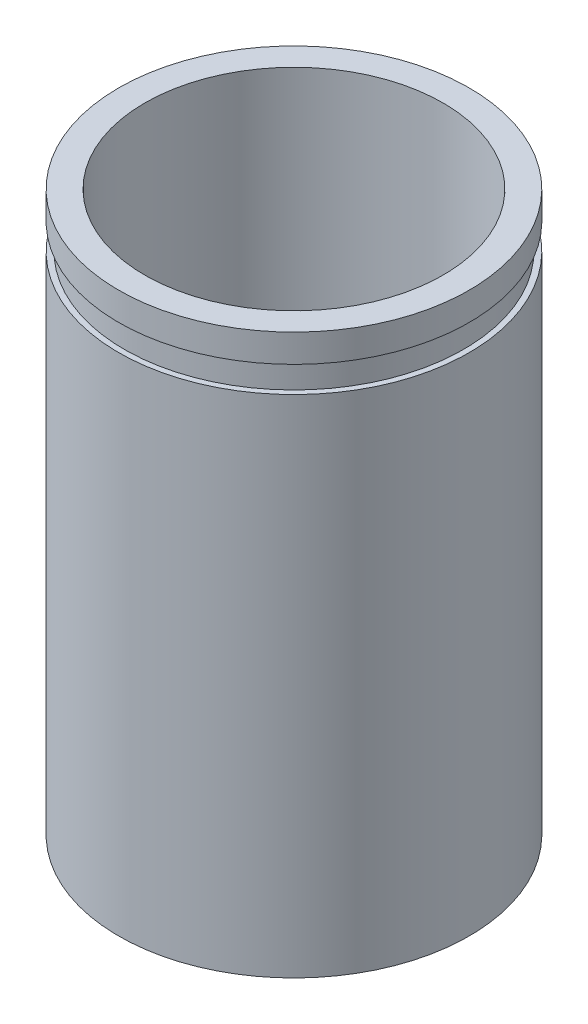
SolidWorks part; units mm, degrees
ref_plane "Front Plane" through (0, 0, 0) normal (0, 0, 1) x (1, 0, 0)
ref_plane "Top Plane" through (0, 0, 0) normal (0, 1, 0) x (1, 0, 0)
ref_plane "Right Plane" through (0, 0, 0) normal (1, 0, 0) x (0, 0, -1)
sketch "Sketch1" plane through (0, 0, 0) normal (0, 0, 1) x (1, 0, 0)
  line L0 (17.2728, 134.2124) -> (24.2728, 134.2124)
  line L1 (24.2728, 134.2124) -> (24.2728, 126.7124)
  line L2 (24.2728, 126.7124) -> (22.7728, 126.7124)
  line L3 (22.7728, 126.7124) -> (22.7728, 119.7124)
  line L4 (22.7728, 119.7124) -> (24.2728, 119.7124)
  line L5 (24.2728, 119.7124) -> (24.2728, -15.7876)
  line L6 (24.2728, -15.7876) -> (17.2728, -15.7876)
  line L7 (17.2728, -15.7876) -> (17.2728, 134.2124)
  line L8 (-22.7272, 134.2124) -> (-22.7272, -15.7876)
  dimension "D1" = 7
  dimension "D2" = 7.5
  dimension "D3" = 1.5
  dimension "D4" = 7
  dimension "D5" = 150
  dimension "D6" = 7
  dimension "D7" = 40
revolve "Revolve1" add sketch "Sketch1" angle 360 about L8
